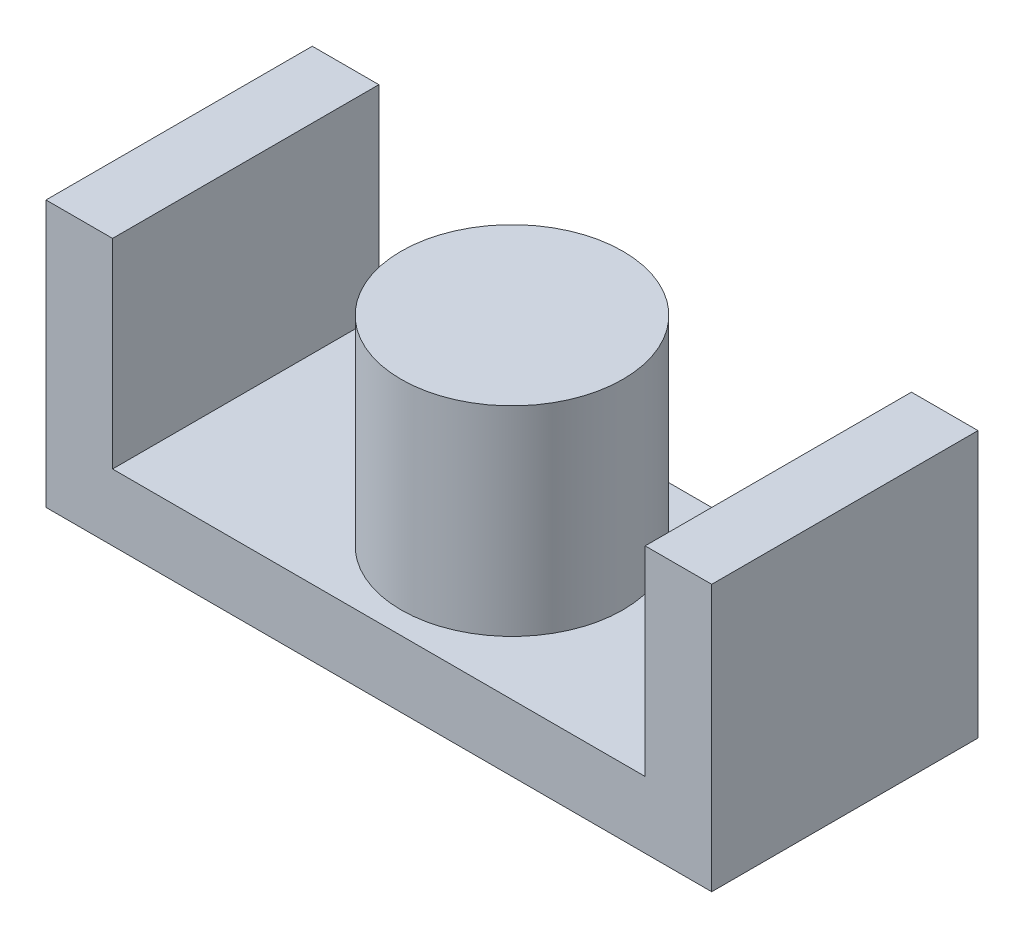
SolidWorks part; units mm, degrees
ref_plane "Front Plane" through (0, 0, 0) normal (1, 0, 0) x (0, 1, 0)
ref_plane "Top Plane" through (0, 0, 0) normal (0, 0, 1) x (0, 1, 0)
ref_plane "Right Plane" through (0, 0, 0) normal (0, 1, 0) x (-1, 0, 0)
sketch "Sketch1" plane through (0, 0, 0) normal (0, 1, 0) x (-1, 0, 0)
  line L1 (0, 0) -> (19.05, 0)
  line L2 (0, 0) -> (0, 7.62)
  line L3 (0, 7.62) -> (19.05, 7.62)
  line L4 (19.05, 0) -> (19.05, 7.62)
  dimension "D1" = 7.62
  dimension "D2" = 19.05
extrude "Boss-Extrude1" add sketch "Sketch1" along normal blind 1.905
sketch "Sketch2" plane through (0, 1.905, 0) normal (0, 1, 0) x (-1, 0, 0)
  line L0 (9.525, 7.62) -> (9.525, 0) construction
  line L1 (19.05, 7.62) -> (0, 7.62) construction
  line L2 (0, 0) -> (19.05, 0) construction
  line L3 (0, 3.81) -> (9.525, 3.81) construction
  line L4 (0, 7.62) -> (0, 0) construction
  line L5 (9.525, 3.81) -> (19.05, 3.81) construction
  line L6 (19.05, 0) -> (19.05, 7.62) construction
  circle A0 centre (9.525, 3.81) radius 3.175
  dimension "D1" = 6.35
extrude "Boss-Extrude2" add sketch "Sketch2" along normal blind 5.715
sketch "Sketch3" plane through (0, 1.905, 0) normal (0, 1, 0) x (-1, 0, 0)
  line L0 (0, 0) -> (19.05, 0) construction
  line L1 (0, 7.62) -> (1.905, 7.62)
  line L2 (0, 7.62) -> (0, 0)
  line L3 (0, 0) -> (1.905, 0)
  line L4 (1.905, 7.62) -> (1.905, 0)
  line L5 (9.525, 7.62) -> (9.525, 0) construction
  line L6 (19.05, 7.62) -> (0, 7.62) construction
  line L7 (19.05, 0) -> (17.145, 0)
  line L8 (17.145, 7.62) -> (17.145, 0)
  line L9 (19.05, 7.62) -> (17.145, 7.62)
  line L10 (19.05, 7.62) -> (19.05, 0)
  dimension "D1" = 1.905
extrude "Boss-Extrude3" add sketch "Sketch3" along normal up to surface (5.715 mm away) up to face at (-9.525, 7.62, 6.985)
equation "\"shaft_d\"= 0.25in"
equation "\"clearance\"= 0.0120in"
equation "\"shrinkage\"= 1.03"
equation "\"shaft_diameter\" = ( \"shaft_d\" )"
equation "\"width\"= 0.3in"
equation "\"length\"= .75in"
equation "\"height\"= .3in"
equation "\"D1@Sketch1\"=\"height\""
equation "\"D2@Sketch1\"=\"length\""
equation "\"D1@Boss-Extrude1\"=\"width\"*.25"
equation "\"D1@Sketch2\"=\"shaft_diameter\""
equation "\"D1@Boss-Extrude2\"=(3/4)*\"width\""
equation "\"D1@Sketch3\"=\"length\"*.1"
equation "\"hole_diameter\" = ( ( \"clearance\" ) + \"shaft_d\" )"
